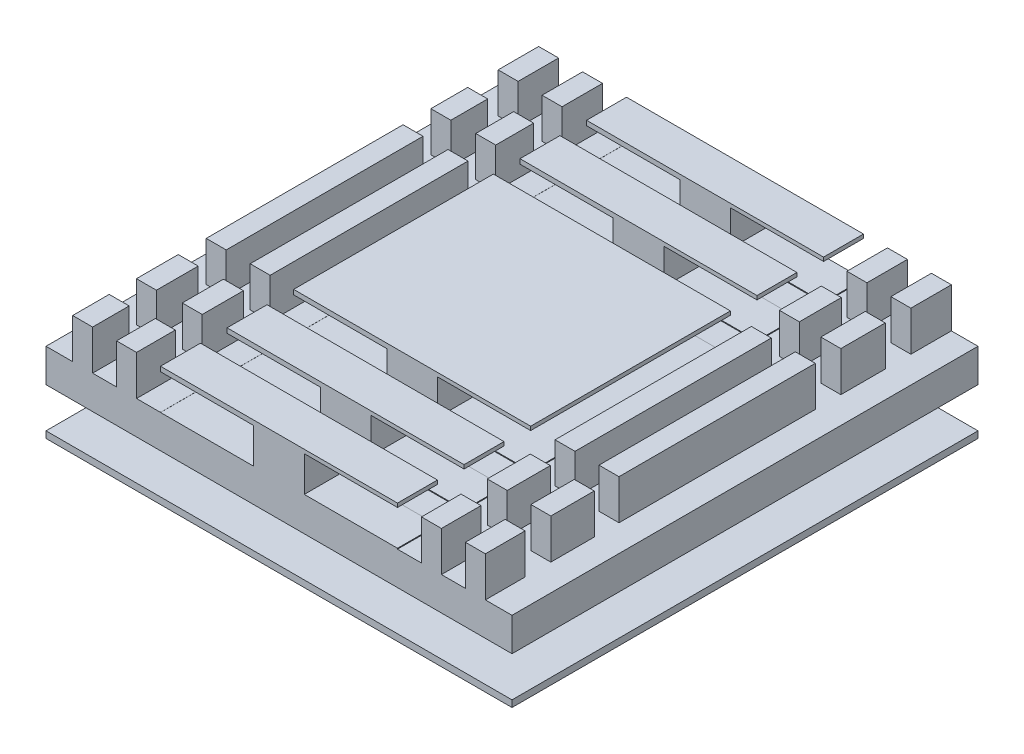
SolidWorks part; units mm, degrees
ref_plane "Front Plane" through (0, 0, 0) normal (0, 0, 1) x (1, 0, 0)
ref_plane "Top Plane" through (0, 0, 0) normal (0, 1, 0) x (1, 0, 0)
ref_plane "Right Plane" through (0, 0, 0) normal (1, 0, 0) x (0, 0, -1)
sketch "Sketch1" plane through (0, 0, 0) normal (0, 1, 0) x (1, 0, 0)
  line L1 (0, 0) -> (35, 0)
  line L2 (0, 0) -> (0, 35)
  line L3 (0, 35) -> (35, 35)
  line L4 (35, 0) -> (35, 35)
  dimension "D1" = 35
  dimension "D2" = 35
extrude "Boss-Extrude1" add sketch "Sketch1" along normal blind 9
sketch "Sketch2" plane through (0, 9, 0) normal (0, 1, 0) x (1, 0, 0)
  line L0 (0, 0) -> (35, 0) construction
  line L1 (35, 35) -> (33, 35)
  line L2 (35, 35) -> (35, 0)
  line L3 (35, 0) -> (33, 0)
  line L4 (33, 35) -> (33, 0)
  line L5 (31.5, 35) -> (29.7, 35)
  line L6 (31.5, 35) -> (31.5, 0)
  line L7 (31.5, 0) -> (29.7, 0)
  line L8 (29.7, 35) -> (29.7, 0)
  line L9 (28.2, 35) -> (26.4, 35)
  line L10 (28.2, 35) -> (28.2, 0)
  line L11 (28.2, 0) -> (26.4, 0)
  line L12 (26.4, 35) -> (26.4, 0)
  line L13 (0, 35) -> (2, 35)
  line L14 (0, 35) -> (0, 0)
  line L15 (0, 0) -> (2, 0)
  line L16 (2, 35) -> (2, 0)
  line L17 (3.5, 35) -> (5.3, 35)
  line L18 (3.5, 35) -> (3.5, 0)
  line L19 (3.5, 0) -> (5.3, 0)
  line L20 (5.3, 35) -> (5.3, 0)
  line L21 (6.8, 35) -> (8.6, 35)
  line L22 (6.8, 35) -> (6.8, 0)
  line L23 (6.8, 0) -> (8.6, 0)
  line L24 (8.6, 35) -> (8.6, 0)
  line L25 (35, 35) -> (0, 35) construction
  dimension "D1" = 2
  dimension "D2" = 2
  dimension "D3" = 1.8
  dimension "D4" = 1.8
  dimension "D5" = 1.8
  dimension "D6" = 1.8
  dimension "D7" = 1.5
  dimension "D8" = 1.5
  dimension "D9" = 1.5
  dimension "D10" = 1.5
  dimension "D11" = 17.8
extrude "Cut-Extrude1" cut sketch "Sketch2" against normal blind 3 contours L2 L1 L4 L3 | L6 L5 L8 L7 | L10 L9 L12 L11 | L22 L21 L24 L23 | L18 L17 L20 L19 | L14 L13 L16 L15
sketch "Sketch3" plane through (35, 0, 0) normal (1, 0, 0) x (0, 0, -1)
  line L0 (0, 0) -> (35, 0) construction
  line L1 (35, 3.5) -> (0, 3.5)
  line L2 (35, 3.5) -> (35, 0.5)
  line L3 (35, 0.5) -> (0, 0.5)
  line L4 (0, 3.5) -> (0, 0.5)
  line L5 (35, 6) -> (0, 6) construction
  line L6 (35, 6) -> (35, 0) construction
  line L7 (0, 6) -> (0, 0) construction
  dimension "D1" = 0.5
  dimension "D2" = 2.5
  dimension "D3" = 3
extrude "Cut-Extrude2" cut sketch "Sketch3" against normal blind 3
sketch "Sketch4" plane through (0, 0, 0) normal (0, 0, 1) x (1, 0, 0)
  line L0 (26.4, 6) -> (26.4, 9) construction
  line L1 (26.4, 8.7127) -> (19.4, 8.7127)
  line L2 (26.4, 8.7127) -> (26.4, 6.0627)
  line L3 (26.4, 6.0627) -> (19.4, 6.0627)
  line L4 (19.4, 8.7127) -> (19.4, 6.0627)
  line L5 (15.6, 8.6432) -> (8.6, 8.6432)
  line L6 (15.6, 8.6432) -> (15.6, 5.9932)
  line L7 (15.6, 5.9932) -> (8.6, 5.9932)
  line L8 (8.6, 8.6432) -> (8.6, 5.9932)
  line L9 (8.6, 6) -> (8.6, 9) construction
  line L10 (0, 6) -> (0, 0) construction
  line L11 (32, 3.5) -> (0, 3.5)
  line L12 (32, 3.5) -> (32, 0.5)
  line L13 (32, 0.5) -> (0, 0.5)
  line L14 (0, 3.5) -> (0, 0.5)
  dimension "D1" = 7
  dimension "D2" = 7
  dimension "D3" = 2.65
  dimension "D4" = 2.65
extrude "Cut-Extrude3" cut sketch "Sketch4" against normal through all contours L2 L1 L4 L3 | L6 L5 L8 L7
sketch "Sketch5" plane through (0, 0, 0) normal (0, 0, 1) x (1, 0, 0)
  line L0 (0, 6) -> (0, 0) construction
  line L1 (32, 3.5) -> (0, 3.5)
  line L2 (32, 3.5) -> (32, 0.5)
  line L3 (32, 0.5) -> (0, 0.5)
  line L4 (0, 3.5) -> (0, 0.5)
extrude "Cut-Extrude4" cut sketch "Sketch5" against normal blind 3
sketch "Sketch6" plane through (0, 9, 0) normal (0, 1, 0) x (1, 0, 0)
  line L0 (8.6, 0) -> (26.4, 0) construction
  line L1 (26.4, 5) -> (8.6, 5)
  line L2 (26.4, 5) -> (26.4, 3)
  line L3 (26.4, 3) -> (8.6, 3)
  line L4 (8.6, 5) -> (8.6, 3)
  line L5 (26.4, 10) -> (8.6, 10)
  line L6 (26.4, 10) -> (26.4, 8)
  line L7 (26.4, 8) -> (8.6, 8)
  line L8 (8.6, 10) -> (8.6, 8)
  line L9 (26.4, 32) -> (8.6, 32)
  line L10 (26.4, 32) -> (26.4, 30)
  line L11 (26.4, 30) -> (8.6, 30)
  line L12 (8.6, 32) -> (8.6, 30)
  line L13 (26.4, 27) -> (8.6, 27)
  line L14 (26.4, 27) -> (26.4, 25)
  line L15 (26.4, 25) -> (8.6, 25)
  line L16 (8.6, 27) -> (8.6, 25)
  line L17 (26.4, 35) -> (8.6, 35) construction
  line L18 (8.6, 35) -> (8.6, 0) construction
  line L19 (26.4, 35) -> (26.4, 0) construction
  line L20 (8.6, 35) -> (8.6, 0) construction
  dimension "D1" = 2
  dimension "D2" = 2
  dimension "D3" = 2
  dimension "D4" = 2
  dimension "D5" = 3
  dimension "D6" = 3
  dimension "D7" = 3
  dimension "D8" = 3
extrude "Cut-Extrude5" cut sketch "Sketch6" against normal blind 3 contours L10 L9 L12 L11 | L14 L13 L16 L15 | L6 L5 L8 L7 | L2 L1 L4 L3
sketch "Sketch7" plane through (0, 9, 0) normal (0, 1, 0) x (1, 0, 0)
  line L0 (28.2, 35) -> (28.2, 0) construction
  line L5 (29.7, 35) -> (29.7, 0) construction
  line L6 (31.5, 35) -> (31.5, 0) construction
  line L11 (33, 35) -> (33, 0) construction
  line L12 (6.8, 35) -> (6.8, 0) construction
  line L13 (6.8, 26.9769) -> (5.3, 26.9769)
  line L14 (6.8, 26.9769) -> (6.8, 24.8969)
  line L15 (6.8, 24.8969) -> (5.3, 24.8969)
  line L16 (5.3, 26.9769) -> (5.3, 24.8969)
  line L17 (5.3, 35) -> (5.3, 0) construction
  line L18 (3.5, 35) -> (3.5, 0) construction
  line L19 (3.5, 26.9066) -> (2, 26.9066)
  line L20 (3.5, 26.9066) -> (3.5, 24.817)
  line L21 (3.5, 24.817) -> (2, 24.817)
  line L22 (2, 26.9066) -> (2, 24.817)
  line L23 (2, 35) -> (2, 0) construction
  line L24 (5.3, 35) -> (5.3, 0) construction
  line L25 (6.8, 31.958) -> (5.3, 31.958)
  line L26 (6.8, 31.958) -> (6.8, 29.8277)
  line L27 (6.8, 29.8277) -> (5.3, 29.8277)
  line L28 (5.3, 31.958) -> (5.3, 29.8277)
  line L29 (29.7, 35) -> (29.7, 0) construction
  line L30 (3.5, 31.958) -> (2, 31.958)
  line L31 (3.5, 31.958) -> (3.5, 29.6736)
  line L32 (3.5, 29.6736) -> (2, 29.6736)
  line L33 (2, 31.958) -> (2, 29.6736)
  line L34 (29.7, 31.958) -> (28.2, 31.958)
  line L35 (29.7, 31.958) -> (29.7, 30.0343)
  line L36 (29.7, 30.0343) -> (28.2, 30.0343)
  line L37 (28.2, 31.958) -> (28.2, 30.0343)
  line L38 (28.2, 35) -> (28.2, 0) construction
  line L39 (31.5, 35) -> (31.5, 0) construction
  line L40 (33, 31.958) -> (31.5, 31.958)
  line L41 (33, 31.958) -> (33, 30.0343)
  line L42 (33, 30.0343) -> (31.5, 30.0343)
  line L43 (31.5, 31.958) -> (31.5, 30.0343)
  line L44 (29.7, 26.8799) -> (28.2, 26.8799)
  line L45 (29.7, 26.8799) -> (29.7, 24.7776)
  line L46 (29.7, 24.7776) -> (28.2, 24.7776)
  line L47 (28.2, 26.8799) -> (28.2, 24.7776)
  line L48 (33, 26.6994) -> (31.5, 26.6994)
  line L49 (33, 26.6994) -> (33, 24.7776)
  line L50 (33, 24.7776) -> (31.5, 24.7776)
  line L51 (31.5, 26.6994) -> (31.5, 24.7776)
  line L52 (6.8, 35) -> (6.8, 0) construction
extrude "Cut-Extrude6" cut sketch "Sketch7" against normal blind 3 contours L31 L30 L33 L32 | L26 L25 L28 L27 | L14 L13 L16 L15 | L20 L19 L22 L21 | L49 L48 L51 L50 | L41 L40 L43 L42 | L35 L34 L37 L36 | L45 L44 L47 L46
sketch "Sketch8" plane through (0, 9, 0) normal (0, 1, 0) x (1, 0, 0)
  line L0 (29.7, 24.7776) -> (29.7, 0) construction
  line L1 (29.7, 10.0334) -> (28.2, 10.0334)
  line L2 (29.7, 10.0334) -> (29.7, 8.1776)
  line L3 (29.7, 8.1776) -> (28.2, 8.1776)
  line L4 (28.2, 10.0334) -> (28.2, 8.1776)
  line L5 (28.2, 24.7776) -> (28.2, 0) construction
  line L6 (33, 24.7776) -> (33, 0) construction
  line L7 (33, 10.0334) -> (31.5, 10.0334)
  line L8 (33, 10.0334) -> (33, 8.1776)
  line L9 (33, 8.1776) -> (31.5, 8.1776)
  line L10 (31.5, 10.0334) -> (31.5, 8.1776)
  line L11 (31.5, 24.7776) -> (31.5, 0) construction
  line L12 (33, 24.7776) -> (33, 0) construction
  line L13 (33, 4.9167) -> (31.5, 4.9167)
  line L14 (33, 4.9167) -> (33, 2.9827)
  line L15 (33, 2.9827) -> (31.5, 2.9827)
  line L16 (31.5, 4.9167) -> (31.5, 2.9827)
  line L17 (29.7, 24.7776) -> (29.7, 0) construction
  line L18 (29.7, 4.9428) -> (28.2, 4.9428)
  line L19 (29.7, 4.9428) -> (29.7, 2.9697)
  line L20 (29.7, 2.9697) -> (28.2, 2.9697)
  line L21 (28.2, 4.9428) -> (28.2, 2.9697)
  line L22 (28.2, 24.7776) -> (28.2, 0) construction
  line L23 (6.8, 24.8969) -> (6.8, 0) construction
  line L24 (6.8, 4.9349) -> (5.3, 4.9349)
  line L25 (6.8, 4.9349) -> (6.8, 2.913)
  line L26 (6.8, 2.913) -> (5.3, 2.913)
  line L27 (5.3, 4.9349) -> (5.3, 2.913)
  line L28 (5.3, 24.8969) -> (5.3, 0) construction
  line L29 (6.8, 24.8969) -> (6.8, 0) construction
  line L30 (6.8, 10.0334) -> (5.3, 10.0334)
  line L31 (6.8, 10.0334) -> (6.8, 8.0273)
  line L32 (6.8, 8.0273) -> (5.3, 8.0273)
  line L33 (5.3, 10.0334) -> (5.3, 8.0273)
  line L34 (3.5, 24.817) -> (3.5, 0) construction
  line L35 (3.5, 10.0334) -> (2, 10.0334)
  line L36 (3.5, 10.0334) -> (3.5, 7.9322)
  line L37 (3.5, 7.9322) -> (2, 7.9322)
  line L38 (2, 10.0334) -> (2, 7.9322)
  line L39 (2, 24.817) -> (2, 0) construction
  line L40 (3.5, 24.817) -> (3.5, 0) construction
  line L41 (3.5, 4.7922) -> (2, 4.7922)
  line L42 (3.5, 4.7922) -> (3.5, 2.7465)
  line L43 (3.5, 2.7465) -> (2, 2.7465)
  line L44 (2, 4.7922) -> (2, 2.7465)
  line L45 (31.5, 24.7776) -> (31.5, 0) construction
extrude "Cut-Extrude7" cut sketch "Sketch8" against normal blind 3 contours L36 L35 L38 L37 | L31 L30 L33 L32 | L25 L24 L27 L26 | L42 L41 L44 L43 | L14 L13 L16 L15 | L19 L18 L21 L20 | L2 L1 L4 L3 | L8 L7 L10 L9
sketch "Sketch9" plane through (0, 0, -35) normal (0, 0, -1) x (-1, 0, 0)
  line L0 (-32, 3.5) -> (-35, 3.5) construction
  line L1 (-32, 3.5) -> (0, 3.5)
  line L2 (-32, 3.5) -> (-32, 0.5)
  line L3 (-32, 0.5) -> (0, 0.5)
  line L4 (0, 3.5) -> (0, 0.5)
  line L5 (-32, 0.5) -> (-32, 3.5) construction
  line L6 (0, 6) -> (0, 0) construction
extrude "Cut-Extrude9" cut sketch "Sketch9" against normal blind 3
sketch "Sketch11" plane through (0, 0, 0) normal (-1, 0, 0) x (0, 0, 1)
  line L1 (-3, 3.5) -> (-32, 3.5)
  line L2 (-3, 3.5) -> (-3, 0.5)
  line L3 (-3, 0.5) -> (-32, 0.5)
  line L4 (-32, 3.5) -> (-32, 0.5)
extrude "Cut-Extrude10" cut sketch "Sketch11" against normal blind 3
